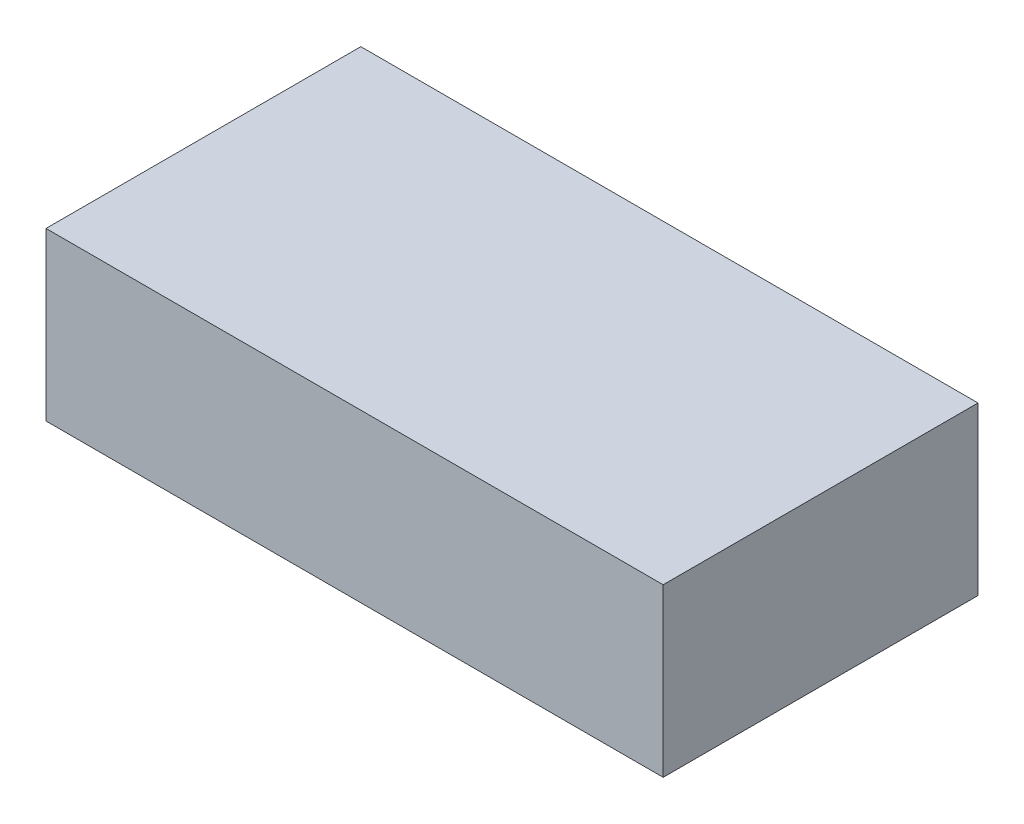
SolidWorks part; units mm, degrees
ref_plane "Front Plane" through (0, 0, 0) normal (0, 0, 1) x (1, 0, 0)
ref_plane "Top Plane" through (0, 0, 0) normal (0, 1, 0) x (1, 0, 0)
ref_plane "Right Plane" through (0, 0, 0) normal (1, 0, 0) x (0, 0, -1)
sketch "Sketch1" plane through (0, 0, 0) normal (0, 1, 0) x (1, 0, 0)
  line L1 (-246.6667, 110.6594) -> (49.3333, 110.6594)
  line L2 (-246.6667, 110.6594) -> (-246.6667, -40.3406)
  line L3 (-246.6667, -40.3406) -> (49.3333, -40.3406)
  line L4 (49.3333, 110.6594) -> (49.3333, -40.3406)
  dimension "D1" = 296
  dimension "D2" = 151
extrude "Boss-Extrude1" add sketch "Sketch1" along normal blind 80 contours L2 L3 L4 L1
